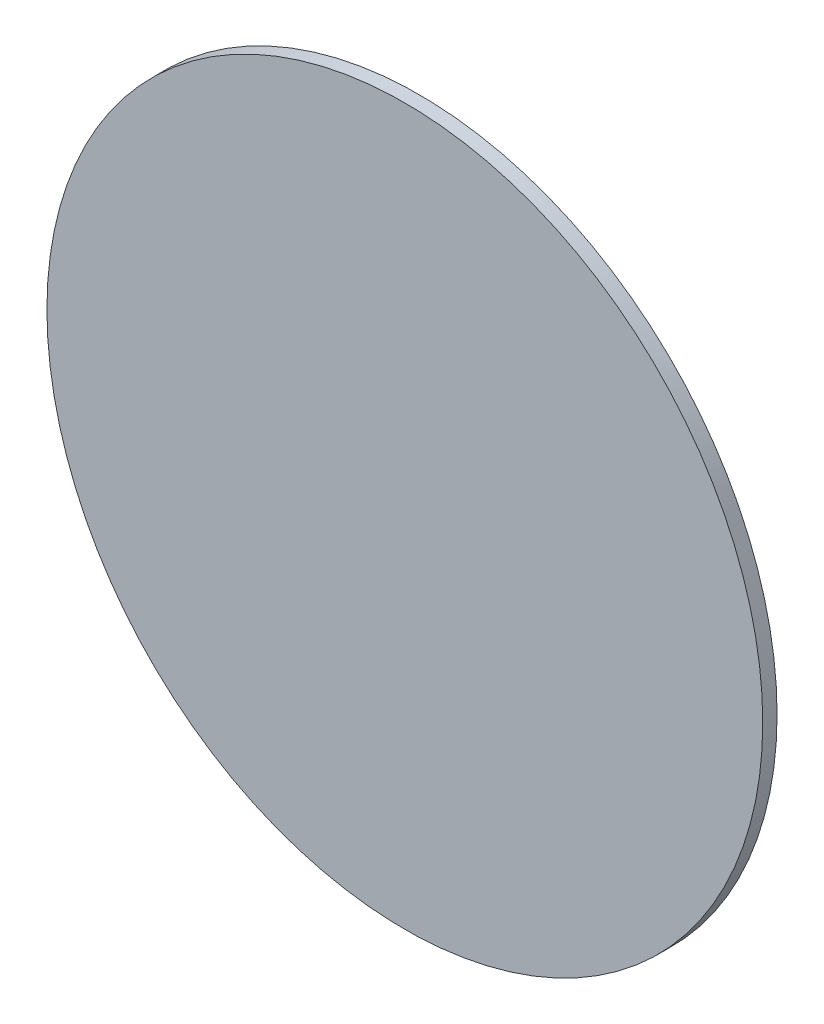
SolidWorks part; units mm, degrees
ref_plane "Front Plane" through (0, 0, 0) normal (0, 0, 1) x (1, 0, 0)
ref_plane "Top Plane" through (0, 0, 0) normal (0, 1, 0) x (1, 0, 0)
ref_plane "Right Plane" through (0, 0, 0) normal (1, 0, 0) x (0, 0, -1)
sketch "Sketch1" plane through (0, 0, 0) normal (0, 0, 1) x (1, 0, 0)
  line L0 (80.0892, 154.6787) -> (400.4459, 154.6787) construction
  circle A0 centre (0, 0) radius 63.5
  dimension "D1" = 127
extrude "Boss-Extrude1" add sketch "Sketch1" along normal blind 2.54
